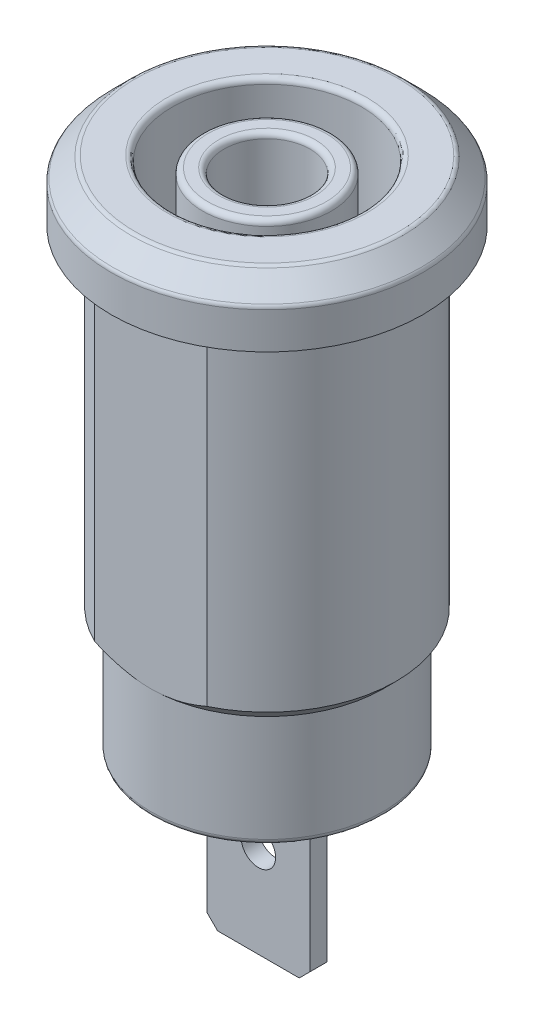
SolidWorks part; units mm, degrees
ref_plane "Front Plane" through (0, 0, 0) normal (0, 0, 1) x (1, 0, 0)
ref_plane "Top Plane" through (0, 0, 0) normal (0, 1, 0) x (1, 0, 0)
ref_plane "Right Plane" through (0, 0, 0) normal (1, 0, 0) x (0, 0, -1)
sketch "Sketch1" plane through (0, 0, 0) normal (0, 0, 1) x (1, 0, 0)
  line L1 (-6.25, 0) -> (-7.25, -1)
  line L2 (-7.25, -1) -> (-7.25, -2.8)
  line L3 (-7.25, -2.8) -> (-6, -2.8)
  line L4 (-6, -2.8) -> (-6, -18.2)
  line L5 (-6, -18.2) -> (-5.4, -18.8)
  line L6 (-5.4, -18.8) -> (-5.4, -24)
  line L7 (-5.4, -24) -> (0, -24)
  line L8 (0, -24) -> (0, 0) construction
  line L9 (-2, -0.5) -> (-2, -20)
  line L10 (-2, -20) -> (0, -21.1547)
  line L11 (0, -21.1547) -> (0, -24)
  line L12 (-4.4, 0) -> (-4.4, -21.5)
  line L13 (-4.4, -21.5) -> (-3, -21.5)
  line L14 (-3, -21.5) -> (-3, -0.5)
  line L15 (-4.4, 0) -> (-6.25, 0)
  line L16 (-3, -0.5) -> (-2, -0.5)
  dimension "D1" = 14.5
  dimension "D2" = 24
  dimension "D3" = 16
  dimension "D4" = 2.8
  dimension "D5" = 10.8
  dimension "D6" = 12
  dimension "D7" = 1
  dimension "D8" = 0.5
  dimension "D9" = 4
  dimension "D10" = 60
  dimension "D11" = 45
  dimension "D12" = 1
  dimension "D13" = 1
  dimension "D14" = 2.5
  dimension "D15" = 19.5
revolve "Revolve1" add sketch "Sketch1" angle 360 about L8
sketch "Sketch2" plane through (0, 0, 0) normal (0, 0, 1) x (1, 0, 0)
  line L0 (-2.4, -24) -> (-2.4, -31.5)
  line L1 (-5.4, -24) -> (5.4, -24) construction
  line L2 (-2.4, -31.5) -> (-1.9, -32)
  line L3 (-1.9, -32) -> (1.9, -32)
  line L4 (1.9, -32) -> (2.4, -31.5)
  line L5 (2.4, -31.5) -> (2.4, -24)
  line L6 (2.4, -24) -> (-2.4, -24)
  line L7 (0, -24) -> (0, 0) construction
  circle A0 centre (0, -27.7) radius 0.8
  dimension "D5" = 4.3
  dimension "D6" = 1.6
  dimension "D1" = 45
  dimension "D2" = 4.8
  dimension "D3" = 8
  dimension "D4" = 0.5
extrude "Boss-Extrude1" add sketch "Sketch2" along normal mid plane 0.8
sketch "Sketch3" plane through (0, -24, 0) normal (0, -1, 0) x (1, 0, 0)
  line L0 (2.6153, 5.4) -> (-2.6153, 5.4)
  line L1 (-2.6153, -5.4) -> (2.6153, -5.4)
  circle A0 centre (0, 0) radius 6 construction
  arc A1 (-2.6153, 5.4) -> (-2.6153, -5.4) centre (0, 0) ccw
  arc A2 (2.6153, -5.4) -> (2.6153, 5.4) centre (0, 0) ccw
  dimension "D1" = 10.8
extrude "Cut-Extrude1" cut sketch "Sketch3" against normal up to surface (21.2 mm away) flip side to cut up to face at (0, -2.8, -6)
fillet "Fillet1" radius 0.25 9 edges at (0, -24, -5.4) (0, -20, -2) (0, -21.5, -3) (0, -21.5, -4.4) (0, 0, -4.4) (0, 0, -6.25) (0, -0.5, -2) (0, -0.5, -3) (0, -1, -7.25)
